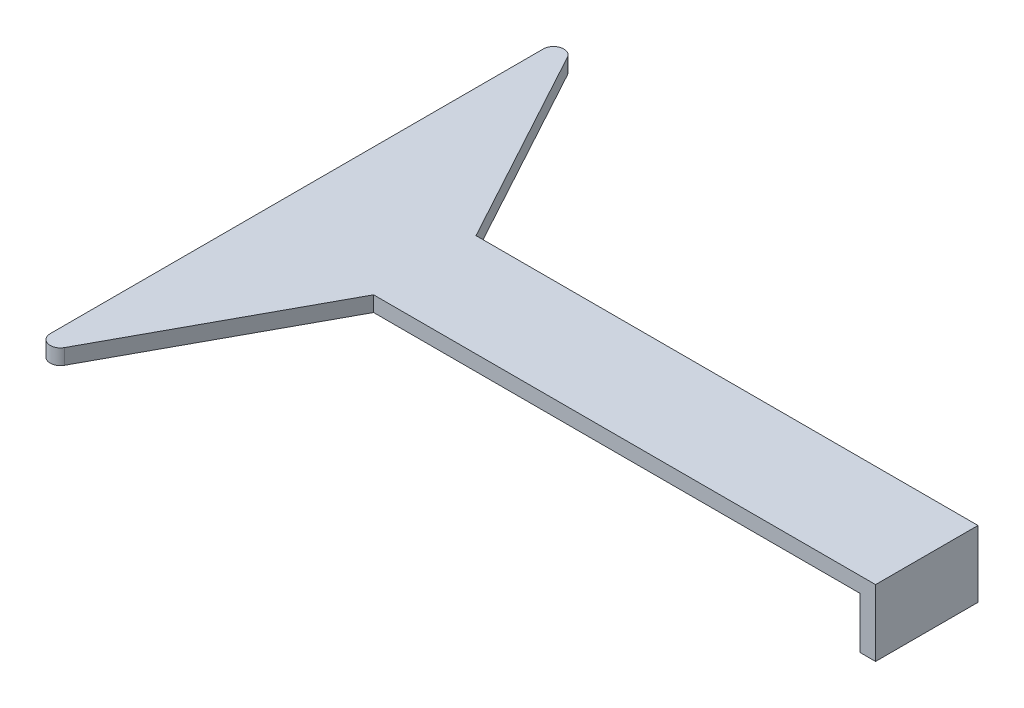
SolidWorks part; units mm, degrees
ref_plane "Front Plane" through (0, 0, 0) normal (0, 0, 1) x (1, 0, 0)
ref_plane "Top Plane" through (0, 0, 0) normal (0, 1, 0) x (1, 0, 0)
ref_plane "Right Plane" through (0, 0, 0) normal (1, 0, 0) x (0, 0, -1)
sketch "Sketch1" plane through (0, 0, 0) normal (0, 1, 0) x (1, 0, 0)
  line L1 (-120, -20) -> (0, -20)
  line L2 (-120, -20) -> (-120, 0)
  line L3 (-120, 0) -> (0, 0)
  line L4 (0, -20) -> (0, 0)
  dimension "D1" = 20
  dimension "D2" = 120
extrude "Boss-Extrude1" add sketch "Sketch1" along normal blind 3
sketch "Sketch2" plane through (0, 0, 0) normal (1, 0, 0) x (0, 0, -1)
  line L0 (0, 3) -> (0, 0) construction
  line L1 (-20, 3) -> (0, 3)
  line L2 (-20, 3) -> (-20, -10)
  line L3 (-20, -10) -> (0, -10)
  line L4 (0, 3) -> (0, -10)
  line L5 (-20, 0) -> (0, 0) construction
  dimension "D1" = 10
extrude "Boss-Extrude2" add sketch "Sketch2" along normal blind 3
sketch "Sketch3" plane through (0, 3, 0) normal (0, 1, 0) x (1, 0, 0)
  line L0 (-120, -20) -> (-120, -58.1316)
  line L1 (-116.2428, -59.0867) -> (-95, -20)
  line L2 (-120, -20) -> (3, -20) construction
  line L3 (-95, -20) -> (-120, -20)
  line L4 (-120, 0) -> (-120, 38.1316)
  line L5 (-116.2428, 39.0867) -> (-95, 0)
  line L6 (3, 0) -> (-120, 0) construction
  line L7 (-95, 0) -> (-120, 0)
  arc A0 (-120, -58.1316) -> (-116.2428, -59.0867) centre (-118, -58.1316) ccw
  arc A1 (-120, 38.1316) -> (-116.2428, 39.0867) centre (-118, 38.1316) cw
  point P8 (-120, -66)
  dimension "D3" = 2
  dimension "D5" = 2
  dimension "D1" = 46
  dimension "D2" = 25
  dimension "D4" = 38.1316
extrude "Boss-Extrude3" add sketch "Sketch3" against normal blind 3
sketch "Sketch5" plane through (0, 0, 0) normal (0, -1, 0) x (1, 0, 0)
  line L0 (-55, 10) -> (-75, 10) construction
  line L1 (-55, 7.5) -> (-75, 7.5)
  line L2 (-55, 12.5) -> (-75, 12.5)
  line L3 (-120, -38.1316) -> (-120, 58.1316) construction
  arc A0 (-55, 7.5) -> (-55, 12.5) centre (-55, 10) ccw
  arc A1 (-75, 12.5) -> (-75, 7.5) centre (-75, 10) ccw
  point P2 (-65, 10)
  point P9 (-120, 10)
  dimension "D1" = 20
  dimension "D2" = 5
  dimension "D3" = 45
extrude "Boss-Extrude4" add sketch "Sketch5" along normal blind 3
